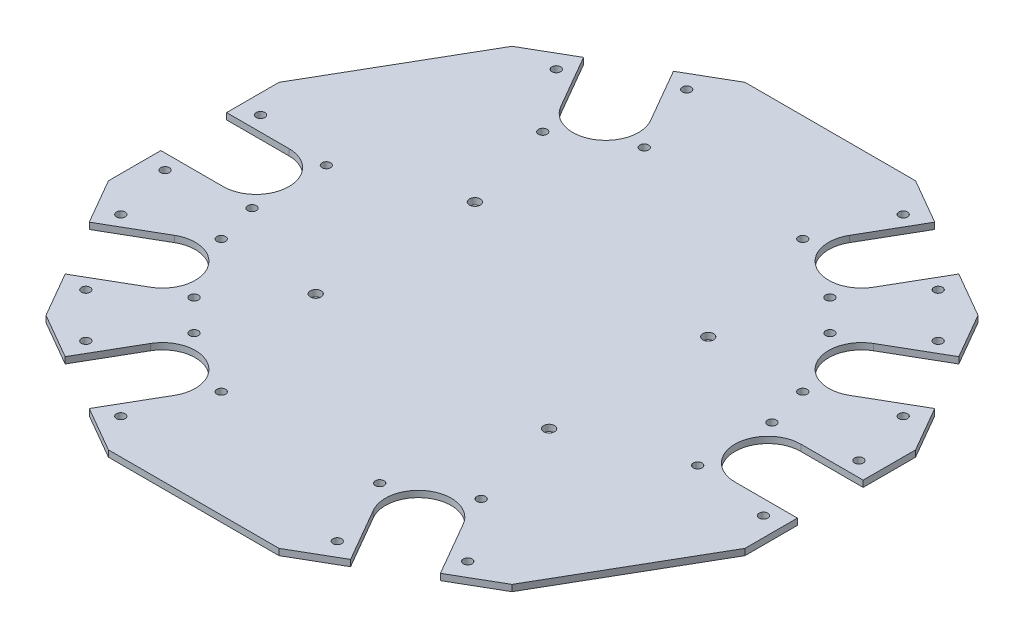
SolidWorks part; units mm, degrees
material "CF-ntbk"
ref_plane "Front Plane" through (0, 0, 0) normal (0, 0, 1) x (1, 0, 0)
ref_plane "Top Plane" through (0, 0, 0) normal (0, 1, 0) x (1, 0, 0)
ref_plane "Right Plane" through (0, 0, 0) normal (1, 0, 0) x (0, 0, -1)
sketch "Sketch1" plane through (0, 0, 0) normal (0, 1, 0) x (1, 0, 0)
  line L19 (150, -40.1924) -> (150, 40.1924)
  line L20 (150, 40.1924) -> (109.8076, 109.8076)
  line L21 (109.8076, 109.8076) -> (40.1924, 150)
  line L22 (40.1924, 150) -> (-40.1924, 150)
  line L23 (-40.1924, 150) -> (-109.8076, 109.8076)
  line L24 (-109.8076, 109.8076) -> (-150, 40.1924)
  line L25 (-150, 40.1924) -> (-150, -40.1924)
  line L26 (-150, -40.1924) -> (-109.8076, -109.8076)
  line L27 (-109.8076, -109.8076) -> (-40.1924, -150)
  line L28 (-40.1924, -150) -> (40.1924, -150)
  line L29 (40.1924, -150) -> (109.8076, -109.8076)
  line L30 (109.8076, -109.8076) -> (150, -40.1924)
  line L33 (-44.2539, 0) -> (44.2539, 0) construction
  circle A0 centre (0, 0) radius 150 construction
  dimension "D1" = 300
  dimension "D2" = 90
extrude "Boss-Extrude1" add sketch "Sketch1" along normal blind 3
sketch "Sketch2" plane through (0, 3, 0) normal (0, 1, 0) x (1, 0, 0)
  line L0 (-79.7985, -138.215) -> (79.7985, 138.215) construction
  line L1 (25.2313, 106.6763) -> (79.8868, 75.1209) construction
  line L2 (-69.8318, 120.9522) -> (69.8318, -120.9522) construction
  line L3 (0, -44.7868) -> (0, 44.7868) construction
  line L5 (-44.2539, 0) -> (44.2539, 0) construction
  line L6 (-150.8166, 0) -> (150.8166, 0) construction
  line L7 (-118.217, -118.217) -> (118.217, 118.217) construction
  line L8 (-102.6144, 102.6144) -> (102.6144, -102.6144) construction
  line L9 (105, 17.5) -> (105, -22.6529) construction
  line L11 (28.2276, -104.9463) -> (76.3829, -77.1439) construction
  circle A0 centre (51.0144, 133.3596) radius 2.05
  circle A1 centre (37.3446, 99.6827) radius 2.05
  circle A2 centre (37.3446, -99.6827) radius 2.05
  circle A3 centre (51.0144, -133.3596) radius 2.05
  circle A4 centre (105, 17.5) radius 2.05
  circle A5 centre (141, 22.5) radius 2.05
  circle A12 centre (105, -17.5) radius 2.05
  circle A13 centre (141, -22.5) radius 2.05
  circle A16 centre (89.9856, -110.8596) radius 2.05
  circle A17 centre (67.6554, -82.1827) radius 2.05
  circle A18 centre (89.9856, 110.8596) radius 2.05
  circle A19 centre (67.6554, 82.1827) radius 2.05
  dimension "D1" = 4.1
  dimension "D3" = 30
  dimension "D5" = 30
  dimension "D10" = 45
  dimension "D11" = 45
  dimension "D4" = 17.5
  dimension "D7" = 105
  dimension "D9" = 22.5
  dimension "D15" = 105
  dimension "D17" = 105
  dimension "D20" = 17.5
  dimension "D21" = 22.5
  dimension "D24" = 17.5
  dimension "D29" = 17.5
  dimension "D12" = 17.5
  dimension "D13" = 22.5
  dimension "D16" = 17.5
  dimension "D22" = 36
  dimension "D23" = 22.5
  dimension "D26" = 36
  dimension "D8" = 36
  dimension "D14" = 36
  dimension "D6" = 22.5
  dimension "D18" = 22.5
  dimension "D19" = 36
  dimension "D25" = 36
extrude "HexCut1" cut sketch "Sketch2" against normal up to surface (3 mm away) up to face at (0, 0, 0)
mirror "HexCut2" about plane through (0, 0, 0) normal (1, 0, 0) of "HexCut1"
sketch "ConstructLines" plane through (0, 3, 0) normal (0, 1, 0) x (1, 0, 0)
  line L0 (0, 121.6855) -> (0, -121.6855) construction
  line L1 (-91.1915, 0) -> (91.1915, 0) construction
  line L2 (-44.2539, 0) -> (44.2539, 0) construction
  line L3 (-70.8661, 122.7437) -> (70.8661, -122.7437) construction
  line L4 (-122.7437, -70.8661) -> (122.7437, 70.8661) construction
  line L5 (-33.6706, -125.6604) -> (33.6706, 125.6604) construction
  line L6 (-132.6309, 35.5383) -> (132.6309, -35.5383) construction
  dimension "D1" = 30
  dimension "D2" = 45
  dimension "D3" = 90
ref_point "Point1"
sketch "Sketch5" plane through (0, 3, 0) normal (0, 1, 0) x (1, 0, 0)
  line L0 (0, 121.6855) -> (0, -121.6855) construction
  line L1 (-91.1915, 0) -> (91.1915, 0) construction
  circle A0 centre (50, 60) radius 1.55
  circle A1 centre (70, 60) radius 1.55
  dimension "D1" = 3.1
  dimension "D2" = 20
  dimension "D3" = 50
  dimension "D4" = 60
  dimension "D5" = 60
extrude "RailMountHoles" [suppressed] cut sketch "Sketch5" against normal up to surface (3 mm away)
pattern_linear "LPattern1" [suppressed] count 2 spacing 120 along (0, 0, 1) count 2 spacing 120 along (1, 0, 0)
sketch "Sketch6" plane through (0, 3, 0) normal (0, 1, 0) x (1, 0, 0)
  line L0 (-126.2708, -72.9025) -> (126.2708, 72.9025) construction
  line L1 (0, 121.6855) -> (0, -121.6855) construction
  line L2 (76.6686, 77.2061) -> (105.5711, 27.1455) construction
  line L3 (-69.5169, 120.4068) -> (69.5169, -120.4068) construction
  circle A0 centre (99.6827, 37.3446) radius 2.05
  circle A1 centre (133.3596, 51.0144) radius 2.05
  circle A2 centre (110.8596, 89.9856) radius 2.05
  circle A3 centre (82.1827, 67.6554) radius 2.05
  dimension "D8" = 36
  dimension "D6" = 22.5
  dimension "D4" = 4.1
  dimension "D1" = 60
  dimension "D2" = 105
  dimension "D5" = 17.5
  dimension "D7" = 17.5
  dimension "D17" = 30
  dimension "D3" = 22.5
  dimension "D9" = 36
extrude "QuadCut1" cut sketch "Sketch6" against normal up to surface (3 mm away) up to face at (-51.0144, 0, -131.3096)
ref_plane "MirrorPlaneQuad" through (0, 0, 0) normal (0.866, 0, -0.5) x (-0.5, 0, -0.866)
mirror "Mirror1" about plane through (0, 0, 0) normal (0.866, 0, -0.5) of "QuadCut1"
sketch "Sketch7" plane through (0, 3, 0) normal (0, 1, 0) x (1, 0, 0)
  line L0 (46.8766, 112.1927) -> (84.3766, 177.1446)
  line L1 (84.3766, 177.1446) -> (111.2234, 161.6446)
  line L2 (111.2234, 161.6446) -> (73.7234, 96.6927)
  line L3 (37.3446, 99.6827) -> (67.6554, 82.1827) construction
  line L4 (105, 17.5) -> (105, -17.5) construction
  line L5 (37.3446, -99.6827) -> (67.6554, -82.1827) construction
  line L6 (46.8766, -112.1927) -> (84.3766, -177.1446)
  line L7 (73.7234, -96.6927) -> (111.2234, -161.6446)
  line L8 (84.3766, -177.1446) -> (111.2234, -161.6446)
  line L9 (120.6, 15.5) -> (160.6, 15.5)
  line L10 (160.6, 15.5) -> (160.6, -15.5)
  line L11 (160.6, -15.5) -> (120.6, -15.5)
  arc A0 (46.8766, 112.1927) -> (73.7234, 96.6927) centre (60.3, 104.4427) ccw
  arc A2 (120.6, 15.5) -> (120.6, -15.5) centre (120.6, 0) ccw
  arc A6 (73.7234, -96.6927) -> (46.8766, -112.1927) centre (60.3, -104.4427) ccw
  circle A10 centre (67.6554, 82.1827) radius 2.05 construction
  dimension "D2" = 75
  dimension "D4" = 31
  dimension "D5" = 15.6
  dimension "D6" = 31
  dimension "D8" = 75
  dimension "D9" = 15.6
  dimension "D10" = 15.6
  dimension "D11" = 40
  dimension "D3" = 2
  dimension "D13" = 2
  dimension "D14" = 31
  dimension "D15" = 2
  dimension "D7" = 2
  dimension "D12" = 2
extrude "Cut-Extrude3" cut sketch "Sketch7" against normal up to surface (3 mm away) up to face at (-82.1827, 0, 69.7054)
mirror "Mirror2" about plane through (0, 0, 0) normal (1, 0, 0) of "Cut-Extrude3"
sketch "Sketch8" plane through (0, 3, 0) normal (0, 1, 0) x (1, 0, 0)
  line L0 (82.1827, 67.6554) -> (99.6827, 37.3446) construction
  line L1 (96.6927, 73.7234) -> (131.3337, 93.7234)
  line L2 (131.3337, 93.7234) -> (146.8337, 66.8766)
  line L3 (146.8337, 66.8766) -> (112.1927, 46.8766)
  arc A0 (96.6927, 73.7234) -> (112.1927, 46.8766) centre (104.4427, 60.3) ccw
  dimension "D1" = 31
  dimension "D2" = 15.6
  dimension "D3" = 40
  dimension "D4" = 2
  dimension "D5" = 2
extrude "Cut-Extrude4" cut sketch "Sketch8" against normal up to surface (3 mm away) up to face at (0, 0, 0)
mirror "Mirror3" about plane through (0, 0, 0) normal (0.866, 0, -0.5) of "Cut-Extrude4"
sketch "Sketch9" plane through (0, 3, 0) normal (0, 1, 0) x (1, 0, 0)
  line L0 (-132.6309, 35.5383) -> (132.6309, -35.5383) construction
  line L1 (-33.6706, -125.6604) -> (33.6706, 125.6604) construction
  circle A0 centre (63.8254, 45.0146) radius 1.55
  circle A1 centre (83.144, 39.8382) radius 1.55
  dimension "D5" = 60
  dimension "D2" = 3.1
  dimension "D1" = 20
  dimension "D3" = 60
  dimension "D4" = 50
extrude "Cut-Extrude5" [suppressed] cut sketch "Sketch9" against normal up to surface (3 mm away)
ref_plane "RailQuadXPlane" through (0, 0, 0) normal (0.2588, 0, -0.9659) x (-0.9659, 0, -0.2588)
ref_plane "RailQuadZPlane" through (0, 0, 0) normal (0.9659, 0, 0.2588) x (0.2588, 0, -0.9659)
mirror "Mirror4" [suppressed] about plane through (0, 0, 0) normal (0.2588, 0, -0.9659)
mirror "Mirror5" [suppressed] about plane through (0, 0, 0) normal (0.9659, 0, 0.2588)
mirror "Mirror6" [suppressed] about plane through (0, 0, 0) normal (0.9659, 0, 0.2588)
sketch "Sketch10" plane through (0, 3, 0) normal (0, 1, 0) x (1, 0, 0)
  line L0 (-44.2539, 0) -> (44.2539, 0) construction
  line L1 (0, -44.7868) -> (0, 44.7868) construction
  circle A0 centre (55, 37.5) radius 2.55
  circle A1 centre (55, -37.5) radius 2.55
  circle A2 centre (-55, 37.5) radius 2.55
  circle A3 centre (-55, -37.5) radius 2.55
  dimension "D1" = 37.5
  dimension "D5" = 5.1
  dimension "D2" = 55
  dimension "D3" = 110
  dimension "D4" = 75
extrude "Cut-Extrude6" cut sketch "Sketch10" against normal up to surface (3 mm away) up to face at (0, 0, 0)
equation "\"ClampHoleDist\"= 36"
equation "\"ClampDistMid\"=105"
equation "\"Length\"= 300"
equation "\"Width\"= 200"
equation "\"RailHoleZDist\"= 60.000000"
equation "\"D5@Sketch5\"=\"RailHoleZDist\""
equation "\"D4@Sketch5\"=\"RailHoleZDist\""
equation "\"RailHoleXDist\"= 50.000000"
equation "\"D3@Sketch5\"=\"RailHoleXDist\""
equation "\"RailHoleSpacing\"= 20"
equation "\"D2@Sketch5\"=\"RailHoleSpacing\""
equation "\"D3@LPattern1\"=\"RailHoleZDist\"*2"
equation "\"D4@LPattern1\"=\"RailHoleXDist\"*2+(\"RailHoleSpacing\")"
equation "\"ClampHoriDist\"=17.5"
equation "\"D4@Sketch2\"=\"ClampHoriDist\""
equation "\"D9@Sketch2\"=\"ClampFrontHoriDist\""
equation "\"D7@Sketch2\"=\"ClampDistMid\""
equation "\"D15@Sketch2\"=\"ClampDistMid\""
equation "\"D17@Sketch2\"=\"ClampDistMid\""
equation "\"D20@Sketch2\"=\"ClampHoriDist\""
equation "\"D21@Sketch2\"=\"ClampFrontHoriDist\""
equation "\"D24@Sketch2\"=\"ClampHoriDist\""
equation "\"D29@Sketch2\"=\"ClampHoriDist\""
equation "\"D12@Sketch2\"=\"ClampHoriDist\""
equation "\"D13@Sketch2\"=\"ClampFrontHoriDist\""
equation "\"ClampHoleSize\"=4.1"
equation "\"D1@Sketch2\"=\"ClampHoleSize\""
equation "\"D16@Sketch2\"=\"ClampHoriDist\""
equation "\"D2@Sketch6\"=\"ClampDistMid\""
equation "\"D4@Sketch6\"=\"ClampHoleSize\""
equation "\"D5@Sketch6\"=\"ClampHoriDist\""
equation "\"D7@Sketch6\"=\"ClampHoriDist\""
equation "\"TubeOutDiam\"= 25.1"
equation "\"D1@Sketch1\"=\"Length\""
equation "\"RailHoleDiam\"=3.1"
equation "\"D1@Sketch5\"=\"RailHoleDiam\""
equation "\"D1@Sketch9\"=\"RailHoleSpacing\""
equation "\"D2@Sketch9\"=\"RailHoleDiam\""
equation "\"D3@Sketch9\"=\"RailHoleZDist\""
equation "\"D4@Sketch9\"=\"RailHoleXDist\""
equation "\"D5@Sketch9\"=\"RailHoleZDist\""
equation "\"SlotDiam\"=31"
equation "\"D4@Sketch7\"=\"SlotDiam\""
equation "\"D3@Sketch7\"=\"ClampHoriDist\" - \"SlotDiam\" / 2"
equation "\"D13@Sketch7\"=\"ClampHoriDist\" - \"SlotDiam\" / 2"
equation "\"MountCutOffset\"=15.6"
equation "\"D5@Sketch7\"=\"MountCutOffset\""
equation "\"D10@Sketch7\"=\"MountCutOffset\""
equation "\"D14@Sketch7\"=\"SlotDiam\""
equation "\"D15@Sketch7\"=\"ClampHoriDist\" - \"SlotDiam\" / 2"
equation "\"D9@Sketch7\"=\"MountCutOffset\""
equation "\"D6@Sketch7\"=\"SlotDiam\""
equation "\"D7@Sketch7\"=\"ClampHoriDist\" - \"SlotDiam\" / 2"
equation "\"D12@Sketch7\"=\"ClampHoriDist\" - \"SlotDiam\" / 2"
equation "\"D2@Sketch8\"=\"MountCutOffset\""
equation "\"D4@Sketch8\"=\"ClampHoriDist\" - \"SlotDiam\" / 2"
equation "\"D5@Sketch8\"=\"ClampHoriDist\" - \"SlotDiam\" / 2"
equation "\"ClampFrontHoriDist\"=22.5"
equation "\"D22@Sketch2\"=\"ClampHoleDist\""
equation "\"D23@Sketch2\"=\"ClampFrontHoriDist\""
equation "\"D6@Sketch2\"=\"ClampFrontHoriDist\""
equation "\"D18@Sketch2\"=\"ClampFrontHoriDist\""
equation "\"D19@Sketch2\"=\"ClampHoleDist\""
equation "\"D25@Sketch2\"=\"ClampHoleDist\""
equation "\"D3@Sketch6\"=\"ClampFrontHoriDist\""
equation "\"D6@Sketch6\"=\"ClampFrontHoriDist\""
equation "\"D8@Sketch6\"=\"ClampHoleDist\""
equation "\"D9@Sketch6\"=\"ClampHoleDist\""
